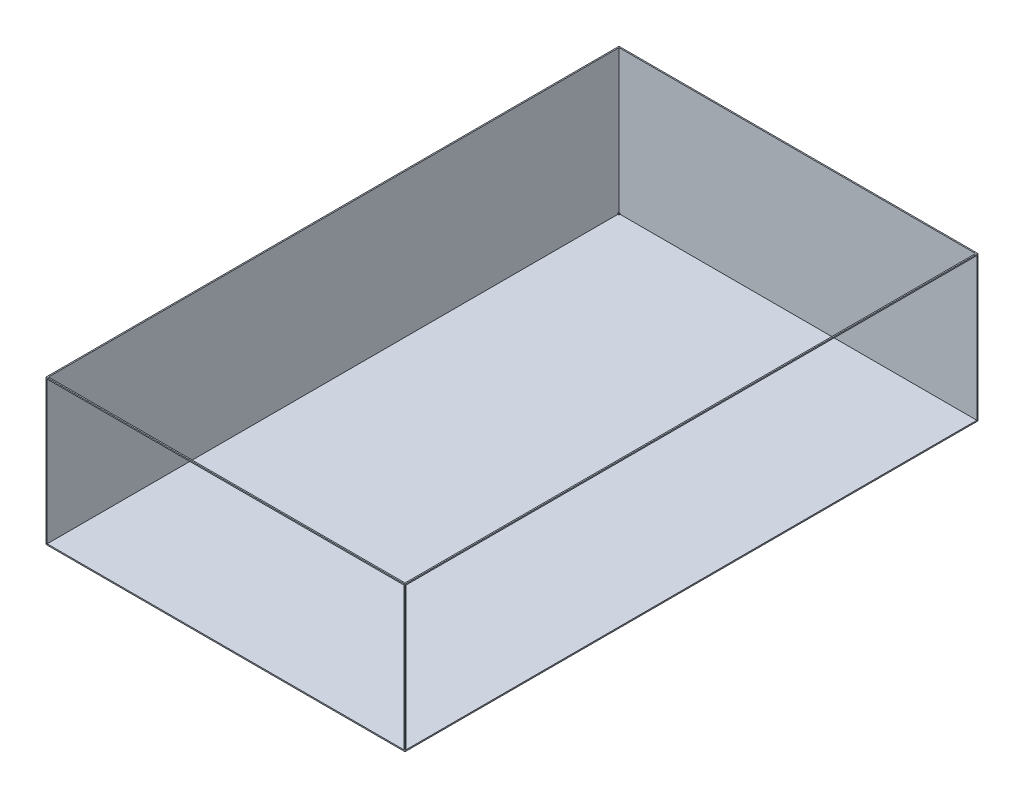
SolidWorks part; units mm, degrees
ref_plane "Front Plane" through (0, 0, 0) normal (0, 0, 1) x (1, 0, 0)
ref_plane "Top Plane" through (0, 0, 0) normal (0, 1, 0) x (1, 0, 0)
ref_plane "Right Plane" through (0, 0, 0) normal (1, 0, 0) x (0, 0, -1)
sketch "Sketch2" plane through (0, 0, 0) normal (0, 0, 1) x (1, 0, 0)
  line L1 (0, 30.5) -> (75.5, 30.5)
  line L2 (0, 30.5) -> (0, 0)
  line L3 (0, 0) -> (75.5, 0)
  line L4 (75.5, 30.5) -> (75.5, 0)
  dimension "D1" = 75.5
  dimension "D2" = 30.5
extrude "Boss-Extrude2" add sketch "Sketch2" against normal blind 120.5
sketch "Sketch4" plane through (0, 0, 0) normal (0, 0, 1) x (1, 0, 0)
  line L0 (0, 30.5) -> (0.25, 30.5)
  line L1 (0.25, 30.25) -> (75.25, 30.25)
  line L2 (0.25, 30.25) -> (0.25, 0.25)
  line L3 (0.25, 0.25) -> (75.25, 0.25)
  line L4 (75.25, 30.25) -> (75.25, 0.25)
  line L5 (75.5, 30.5) -> (0, 30.5) construction
  line L6 (0.25, 30.5) -> (0.25, 30.25)
  dimension "D1" = 75
  dimension "D2" = 30
  dimension "D3" = 0.25
  dimension "D4" = 0.25
extrude "Cut-Extrude1" cut sketch "Sketch4" against normal blind 120 contours L4 L1 L2 L3
sketch "Sketch5" plane through (0, 30.5, 0) normal (0, 1, 0) x (1, 0, 0)
  line L0 (0, 0) -> (0.25, 0)
  line L1 (0.25, 120.25) -> (75.25, 120.25)
  line L2 (0.25, 120.25) -> (0.25, 0.25)
  line L3 (0.25, 0.25) -> (75.25, 0.25)
  line L4 (75.25, 120.25) -> (75.25, 0.25)
  line L5 (75.5, 0) -> (0, 0) construction
  line L6 (0.25, 0) -> (0.25, 0.25)
  dimension "D1" = 75
  dimension "D2" = 120
  dimension "D3" = 0.25
  dimension "D4" = 0.25
extrude "Cut-Extrude2" cut sketch "Sketch5" against normal blind 30 contours L4 L1 L2 L3
sketch "Sketch6" plane through (75.5, 0, 0) normal (1, 0, 0) x (0, 0, -1)
  line L0 (0, 0) -> (0.25, 0)
  line L1 (120.5, 0) -> (0, 0) construction
  line L2 (0.25, 0) -> (0.25, 0.25)
  line L4 (0.25, 30.25) -> (120.25, 30.25)
  line L5 (0.25, 30.25) -> (0.25, 0.25)
  line L6 (0.25, 0.25) -> (120.25, 0.25)
  line L7 (120.25, 30.25) -> (120.25, 0.25)
  dimension "D1" = 0.25
  dimension "D2" = 0.25
  dimension "D3" = 120
  dimension "D4" = 30
extrude "Cut-Extrude3" cut sketch "Sketch6" against normal blind 75 contours L7 L4 L5 L6
